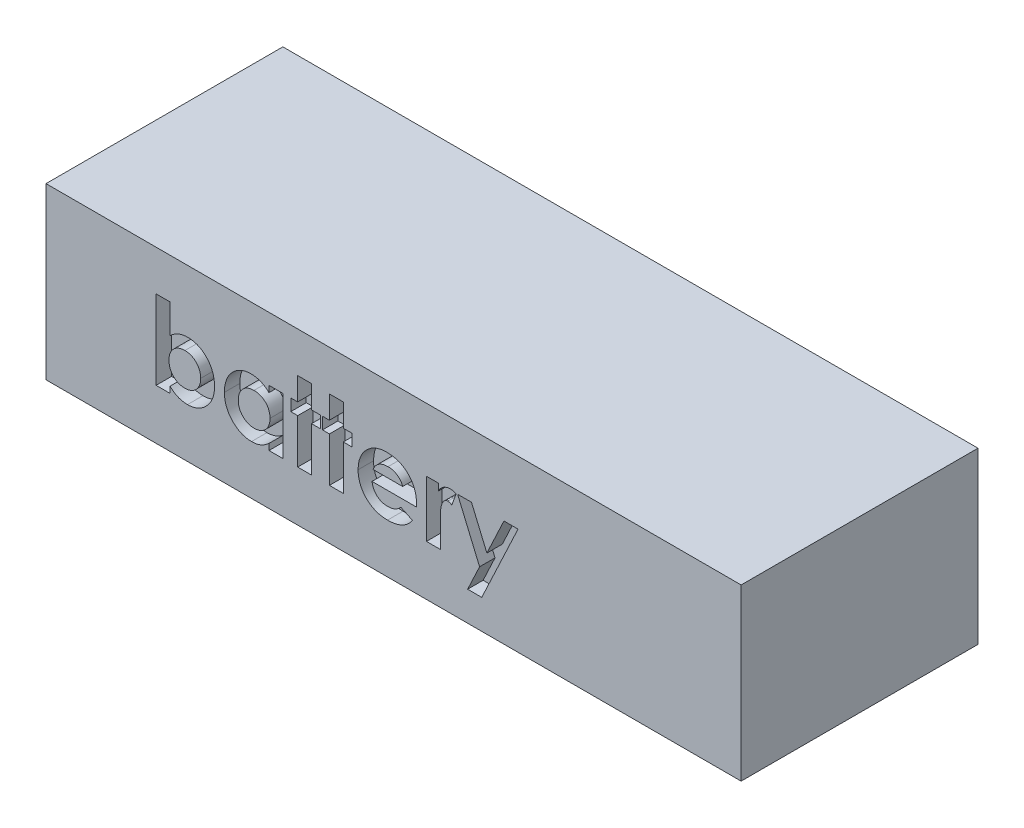
SolidWorks part; units mm, degrees
ref_plane "正面" through (0, 0, 0) normal (0, 0, 1) x (1, 0, 0)
ref_plane "平面" through (0, 0, 0) normal (0, 1, 0) x (1, 0, 0)
ref_plane "右側面" through (0, 0, 0) normal (1, 0, 0) x (0, 0, -1)
sketch "ｽｹｯﾁ1" plane through (0, 0, 0) normal (0, 0, 1) x (1, 0, 0)
  line L1 (0, 0) -> (135, 0)
  line L2 (0, 0) -> (0, 33)
  line L3 (0, 33) -> (135, 33)
  line L4 (135, 0) -> (135, 33)
  dimension "D1" = 135
  dimension "D2" = 33
extrude "ﾎﾞｽ - 押し出し1" add sketch "ｽｹｯﾁ1" along normal blind 46
sketch "ｽｹｯﾁ2" plane through (0, 0, 46) normal (0, 0, 1) x (1, 0, 0)
  text T0 "<b>battery</b>" font "Century Gothic" height 15
extrude "ｶｯﾄ - 押し出し1" cut sketch "ｽｹｯﾁ2" against normal blind 3
